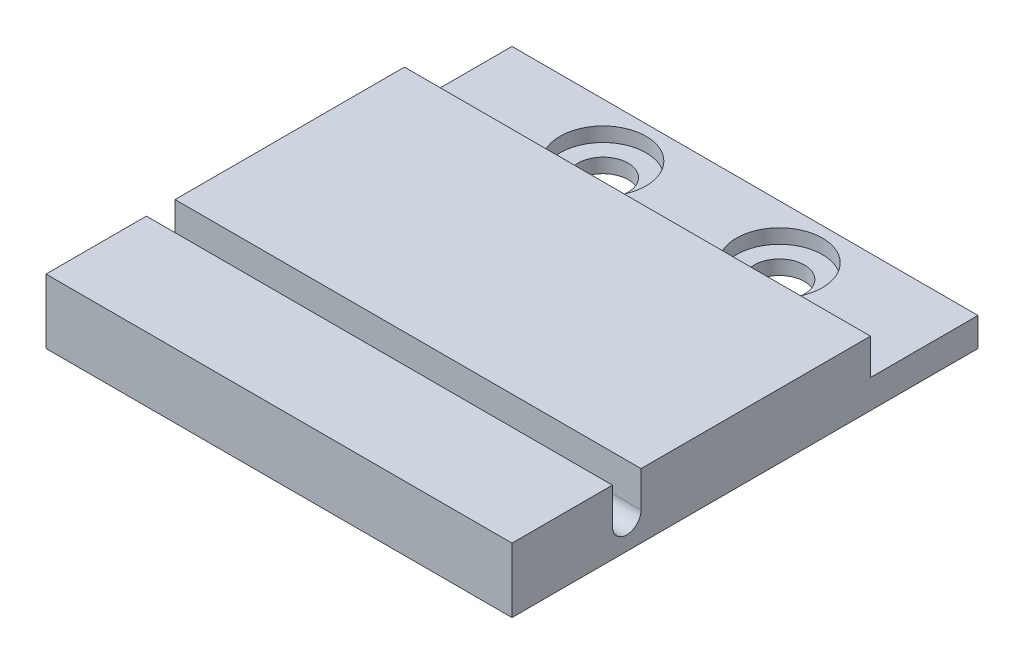
SolidWorks part; units mm, degrees
ref_plane "前视基准面" through (0, 0, 0) normal (0, 0, 1) x (1, 0, 0)
ref_plane "上视基准面" through (0, 0, 0) normal (0, 1, 0) x (1, 0, 0)
ref_plane "右视基准面" through (0, 0, 0) normal (1, 0, 0) x (0, 0, -1)
other "Configuration Table"
sketch "草图1" plane through (0, 0, 0) normal (0, 1, 0) x (1, 0, 0)
  line L1 (-32.5, 32.5) -> (32.5, 32.5)
  line L2 (-32.5, 32.5) -> (-32.5, -32.5)
  line L3 (-32.5, -32.5) -> (32.5, -32.5)
  line L4 (32.5, 32.5) -> (32.5, -32.5)
  line L5 (-32.5, 32.5) -> (32.5, -32.5) construction
  line L6 (-32.5, -32.5) -> (32.5, 32.5) construction
  point P0 (0, 0)
  dimension "D1" = 65
  dimension "D2" = 65
extrude "凸台-拉伸1" add sketch "草图1" along normal blind 4
sketch "草图2" plane through (0, 4, 0) normal (0, 1, 0) x (1, 0, 0)
  line L0 (-32.5, 32.5) -> (-32.5, -32.5) construction
  line L1 (32.5, -32.5) -> (32.5, 32.5) construction
  line L2 (32.5, 32.5) -> (-32.5, 32.5) construction
  circle A0 centre (-12.3, 25) radius 3.5
  circle A1 centre (12.3, 25) radius 3.5
  dimension "D1" = 7
  dimension "D2" = 7
  dimension "D3" = 20.2
  dimension "D4" = 20.2
  dimension "D5" = 7.5
  dimension "D6" = 7.5
extrude "切除-拉伸1" cut sketch "草图2" against normal through all
sketch "草图3" plane through (0, 4, 0) normal (0, 1, 0) x (1, 0, 0)
  circle A0 centre (-12.3, 25) radius 6
  circle A1 centre (12.3, 25) radius 6
  dimension "D1" = 12
  dimension "D2" = 12
extrude "切除-拉伸2" cut sketch "草图3" against normal blind 2
sketch "草图4" plane through (0, 4, 0) normal (0, 1, 0) x (1, 0, 0)
  line L0 (-32.5, 32.5) -> (-32.5, -32.5) construction
  line L1 (-32.5, 17.5) -> (32.5, 17.5)
  line L2 (-32.5, 17.5) -> (-32.5, -32.5)
  line L3 (-32.5, -32.5) -> (32.5, -32.5)
  line L4 (32.5, 17.5) -> (32.5, -32.5)
  line L5 (32.5, 32.5) -> (-32.5, 32.5) construction
  dimension "D1" = 15
extrude "凸台-拉伸2" add sketch "草图4" along normal blind 5
sketch "草图5" plane through (32.5, 0, 0) normal (1, 0, 0) x (0, 0, -1)
  line L0 (-32.5, 9) -> (17.5, 9) construction
  line L1 (-18.5, 9) -> (-14.5, 9)
  line L2 (-18.5, 9) -> (-18.5, 4)
  line L3 (-18.5, 4) -> (-14.5, 4)
  line L4 (-14.5, 9) -> (-14.5, 4)
  line L5 (-32.5, 9) -> (-32.5, 0) construction
  dimension "D1" = 5
  dimension "D2" = 4
  dimension "D3" = 14
extrude "切除-拉伸3" cut sketch "草图5" against normal through all
sketch "草图6" plane through (32.5, 0, 0) normal (1, 0, 0) x (0, 0, -1)
  line L0 (-18.5, 4) -> (-14.5, 4) construction
  circle A0 centre (-16.5, 4) radius 2
extrude "切除-拉伸4" cut sketch "草图6" against normal through all
